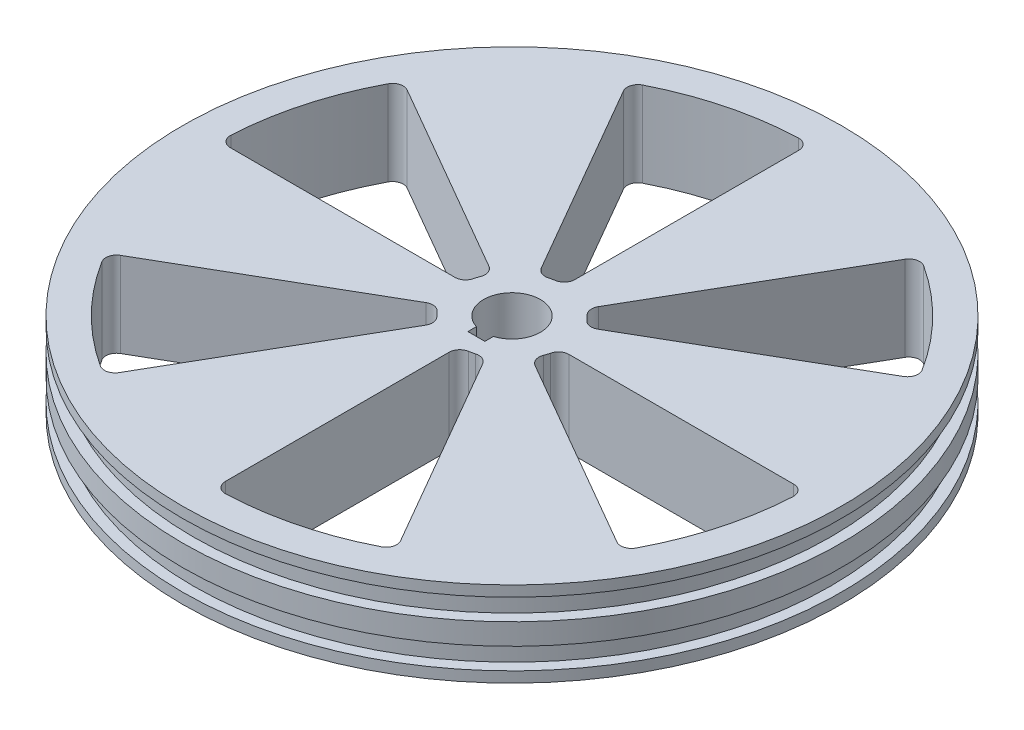
SolidWorks part; units mm, degrees
material "1023 Carbon Steel Sheet (SS)"
ref_plane "Front Plane" through (0, 0, 0) normal (0, 0, 1) x (1, 0, 0)
ref_plane "Top Plane" through (0, 0, 0) normal (0, 1, 0) x (1, 0, 0)
ref_plane "Right Plane" through (0, 0, 0) normal (1, 0, 0) x (0, 0, -1)
sketch "Sketch1" plane through (0, 0, 0) normal (1, 0, 0) x (0, 0, -1)
  line L0 (0, 0) -> (0, 96.0725) construction
  line L1 (13.3686, 0) -> (155, 0)
  line L2 (155, 0) -> (155, 5)
  line L3 (155, 5) -> (150, 5)
  line L4 (150, 5) -> (150, 15)
  line L5 (150, 35) -> (155, 35)
  line L6 (155, 35) -> (155, 40)
  line L7 (155, 40) -> (13.3686, 40)
  line L8 (13.3686, 40) -> (13.3686, 0)
  line L9 (150, 25) -> (155, 25)
  line L10 (155, 25) -> (155, 15)
  line L11 (155, 15) -> (150, 15)
  line L12 (150, 25) -> (150, 35)
  dimension "D1" = 150
  dimension "D2" = 5
  dimension "D3" = 5
  dimension "D4" = 10
revolve "Revolve1" add sketch "Sketch1" angle 360 about L0
sketch "Sketch2" plane through (0, 0, 0) normal (0, -1, 0) x (1, 0, 0)
  line L1 (-4, 16.7561) -> (4, 16.7561)
  line L2 (-4, 16.7561) -> (-4, 12.7561)
  line L4 (4, 16.7561) -> (4, 12.7561)
  line L5 (-4, 16.7561) -> (4, 12.7561) construction
  line L6 (-4, 12.7561) -> (4, 16.7561) construction
  circle A0 centre (0, 0) radius 13.3686 construction
  arc A1 (4, 12.7561) -> (-4, 12.7561) centre (0, 0) ccw
  point P0 (0, 14.7561)
  point P6 (0, 16.7561)
extrude "Cut-Extrude1" cut sketch "Sketch2" against normal through all
sketch "Sketch3" plane through (0, 0, 0) normal (0, -1, 0) x (1, 0, 0)
  line L0 (0, 29.5804) -> (0, 134.8221)
  line L1 (12.5829, 26.3425) -> (65.3898, 117.8068)
  line L2 (25.6174, 14.7902) -> (116.7594, 67.4111)
  line L3 (29.1047, 2.2742) -> (134.7186, 2.2742)
  line L4 (25.6174, -14.7902) -> (116.7594, -67.4111)
  line L5 (16.5219, -24.0684) -> (69.3288, -115.5326)
  line L6 (0, -29.5804) -> (0, -134.8221)
  line L7 (-12.5829, -26.3425) -> (-65.3898, -117.8068)
  line L8 (-25.6174, -14.7902) -> (-116.7594, -67.4111)
  line L9 (-29.1047, -2.2742) -> (-134.7186, -2.2742)
  line L10 (-25.6174, 14.7902) -> (-116.7594, 67.4111)
  line L11 (-16.5219, 24.0684) -> (-69.3288, 115.5326)
  arc A0 (6.8773, 24.0355) -> (4.1667, 24.6503) centre (0, 0) ccw
  arc A1 (63.3226, 124.7654) -> (5.1853, 139.8187) centre (0, 0) ccw
  arc A2 (6.8773, 24.0355) -> (12.5829, 26.3425) centre (8.2527, 28.8425) ccw
  arc A3 (0, 29.5804) -> (4.1667, 24.6503) centre (5, 29.5804) ccw
  arc A4 (63.3226, 124.7654) -> (65.3898, 117.8068) centre (61.0597, 120.3068) cw
  arc A5 (0, 134.8221) -> (5.1853, 139.8187) centre (5, 134.8221) cw
  arc A6 (139.7113, 7.5438) -> (123.6792, 65.4188) centre (0, 0) ccw
  arc A7 (139.7113, 7.5438) -> (134.7186, 2.2742) centre (134.7186, 7.2742) cw
  arc A8 (116.7594, 67.4111) -> (123.6792, 65.4188) centre (119.2594, 63.0809) cw
  arc A9 (25.6174, 14.7902) -> (23.4311, 8.7167) centre (28.1174, 10.4601) ccw
  arc A10 (24.254, 6.0618) -> (23.4311, 8.7167) centre (0, 0) ccw
  arc A11 (24.254, 6.0618) -> (29.1047, 2.2742) centre (29.1047, 7.2742) ccw
  arc A12 (76.3888, -117.2217) -> (118.4939, -74.4) centre (0, 0) ccw
  arc A13 (76.3888, -117.2217) -> (69.3288, -115.5326) centre (73.6589, -113.0326) cw
  arc A14 (116.7594, -67.4111) -> (118.4939, -74.4) centre (114.2594, -71.7412) cw
  arc A15 (25.6174, -14.7902) -> (19.2645, -15.9336) centre (23.1174, -19.1203) ccw
  arc A16 (17.3767, -17.9736) -> (19.2645, -15.9336) centre (0, 0) ccw
  arc A17 (17.3767, -17.9736) -> (16.5219, -24.0684) centre (20.852, -21.5684) ccw
  arc A18 (-63.3226, -124.7654) -> (-5.1853, -139.8187) centre (0, 0) ccw
  arc A19 (-63.3226, -124.7654) -> (-65.3898, -117.8068) centre (-61.0597, -120.3068) cw
  arc A20 (0, -134.8221) -> (-5.1853, -139.8187) centre (-5, -134.8221) cw
  arc A21 (0, -29.5804) -> (-4.1667, -24.6503) centre (-5, -29.5804) ccw
  arc A22 (-6.8773, -24.0355) -> (-4.1667, -24.6503) centre (0, 0) ccw
  arc A23 (-6.8773, -24.0355) -> (-12.5829, -26.3425) centre (-8.2527, -28.8425) ccw
  arc A24 (-139.7113, -7.5438) -> (-123.6792, -65.4188) centre (0, 0) ccw
  arc A25 (-139.7113, -7.5438) -> (-134.7186, -2.2742) centre (-134.7186, -7.2742) cw
  arc A26 (-116.7594, -67.4111) -> (-123.6792, -65.4188) centre (-119.2594, -63.0809) cw
  arc A27 (-25.6174, -14.7902) -> (-23.4311, -8.7167) centre (-28.1174, -10.4601) ccw
  arc A28 (-24.254, -6.0618) -> (-23.4311, -8.7167) centre (0, 0) ccw
  arc A29 (-24.254, -6.0618) -> (-29.1047, -2.2742) centre (-29.1047, -7.2742) ccw
  arc A30 (-76.3888, 117.2217) -> (-118.4939, 74.4) centre (0, 0) ccw
  arc A31 (-76.3888, 117.2217) -> (-69.3288, 115.5326) centre (-73.6589, 113.0326) cw
  arc A32 (-116.7594, 67.4111) -> (-118.4939, 74.4) centre (-114.2594, 71.7412) cw
  arc A33 (-25.6174, 14.7902) -> (-19.2645, 15.9336) centre (-23.1174, 19.1203) ccw
  arc A34 (-17.3767, 17.9736) -> (-19.2645, 15.9336) centre (0, 0) ccw
  arc A35 (-17.3767, 17.9736) -> (-16.5219, 24.0684) centre (-20.852, 21.5684) ccw
  point P11 (0, 25)
  point P78 (0, 0)
  dimension "D1" = 30
  dimension "D2" = 5
  dimension "D3" = 6
extrude "Cut-Extrude2" cut sketch "Sketch3" against normal through all
